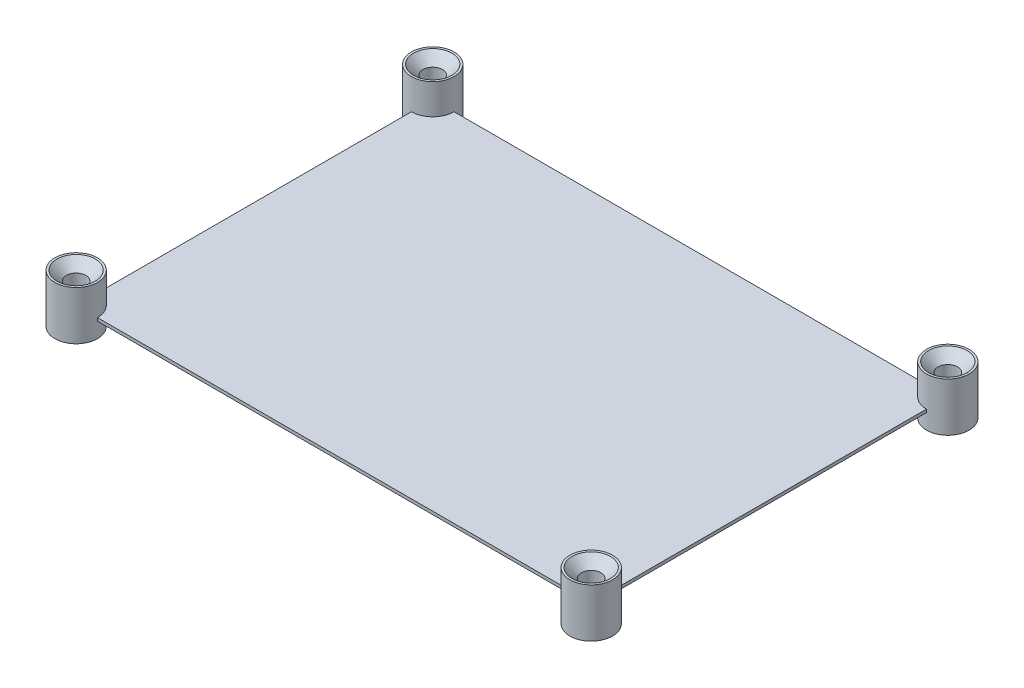
SolidWorks part; units mm, degrees
ref_plane "Front Plane" through (0, 0, 0) normal (0, 0, 1) x (1, 0, 0)
ref_plane "Top Plane" through (0, 0, 0) normal (0, 1, 0) x (1, 0, 0)
ref_plane "Right Plane" through (0, 0, 0) normal (1, 0, 0) x (0, 0, -1)
sketch "Sketch2" plane through (0, 0, 0) normal (0, 1, 0) x (1, 0, 0)
  line L1 (0, 0) -> (-84.5, 0)
  line L2 (0, 0) -> (0, -58.5)
  line L3 (0, -58.5) -> (-84.5, -58.5)
  line L4 (-84.5, 0) -> (-84.5, -58.5)
extrude "Boss-Extrude1" add sketch "Sketch2" along normal blind 0.5
sketch "Sketch3" plane through (0, 0.5, 0) normal (0, 1, 0) x (1, 0, 0)
  circle A0 centre (-84.5, 0) radius 3.5
  circle A1 centre (-84.5, 0) radius 3.5
sketch "Sketch5" plane through (0, 0.5, 0) normal (0, 1, 0) x (1, 0, 0)
  line L0 (-84.5, 0) -> (-84.5, -58.5) construction
  circle A0 centre (-84.5, -58.5) radius 3.5
  circle A1 centre (-84.5, -58.5) radius 3.5
sketch "Sketch6" plane through (0, 0.5, 0) normal (0, 1, 0) x (1, 0, 0)
  circle A0 centre (0, -58.5) radius 3.5
  circle A1 centre (0, -58.5) radius 3.5
sketch "Sketch7" plane through (0, 0.5, 0) normal (0, 1, 0) x (1, 0, 0)
  circle A0 centre (0, 0) radius 3.5
  circle A1 centre (0, 0) radius 3.5
extrude "Boss-Extrude2" add sketch "Sketch3" along normal blind 5 and the other way blind 3 contours A0
extrude "Boss-Extrude3" add sketch "Sketch5" along normal blind 5 and the other way blind 3 contours A0
extrude "Boss-Extrude4" add sketch "Sketch6" along normal blind 5 and the other way blind 3 contours A0
extrude "Boss-Extrude5" add sketch "Sketch7" along normal blind 5 and the other way blind 3 contours A0
hole_wizard "CSK for M3 Flat Head Machine Screw1" positions "Sketch9" profile "Sketch10" countersink size "M3" standard "ANSI Metric"
sketch "Sketch9" plane through (0, 5.5, 0) normal (0, 1, 0) x (1, 0, 0)
  point P0 (-84.5, 0)
sketch "Sketch10" plane through (-84.5, 5.5, 0) normal (1, 0, 0) x (0, 0, 1)
  line L0 (0, 0) -> (0, 14)
  line L1 (0, 14) -> (1.6, 13.0386)
  line L2 (1.6, 13.0386) -> (1.6, 1.55)
  line L3 (1.6, 1.55) -> (3.15, 0)
  line L5 (3.15, 0) -> (0, 0)
  line L6 (-1.6, 1.55) -> (-3.15, 0) construction
  line L10 (0, 14) -> (-1.6, 13.0386) construction
  line L11 (0, -6.35) -> (0, 107.95) construction
  dimension "Hole Dia." = 3.2
  dimension "Hole Depth" = 14
  dimension "Near C'Sink Dia." = 6.3
  dimension "Near C'Sink Angle" = 90
  dimension "Drill Angle" = 118
hole_wizard "CSK for M3 Flat Head Machine Screw2" positions "Sketch11" profile "Sketch12" countersink size "M3" standard "ANSI Metric"
sketch "Sketch11" plane through (0, 5.5, 0) normal (0, 1, 0) x (1, 0, 0)
  point P0 (-84.5, -58.5)
sketch "Sketch12" plane through (-84.5, 5.5, 58.5) normal (1, 0, 0) x (0, 0, 1)
  line L0 (0, 0) -> (0, 14)
  line L1 (0, 14) -> (1.6, 13.0386)
  line L2 (1.6, 13.0386) -> (1.6, 1.55)
  line L3 (1.6, 1.55) -> (3.15, 0)
  line L5 (3.15, 0) -> (0, 0)
  line L6 (-1.6, 1.55) -> (-3.15, 0) construction
  line L10 (0, 14) -> (-1.6, 13.0386) construction
  line L11 (0, -6.35) -> (0, 107.95) construction
  dimension "Hole Dia." = 3.2
  dimension "Hole Depth" = 14
  dimension "Near C'Sink Dia." = 6.3
  dimension "Near C'Sink Angle" = 90
  dimension "Drill Angle" = 118
hole_wizard "CSK for M3 Flat Head Machine Screw3" positions "Sketch15" profile "Sketch16" countersink size "M3" standard "ANSI Metric"
sketch "Sketch15" plane through (0, 5.5, 0) normal (0, 1, 0) x (1, 0, 0)
  point P0 (0, 0)
sketch "Sketch16" plane through (0, 5.5, 0) normal (1, 0, 0) x (0, 0, 1)
  line L0 (0, 0) -> (0, 14)
  line L1 (0, 14) -> (1.6, 13.0386)
  line L2 (1.6, 13.0386) -> (1.6, 1.55)
  line L3 (1.6, 1.55) -> (3.15, 0)
  line L5 (3.15, 0) -> (0, 0)
  line L6 (-1.6, 1.55) -> (-3.15, 0) construction
  line L10 (0, 14) -> (-1.6, 13.0386) construction
  line L11 (0, -6.35) -> (0, 107.95) construction
  dimension "Hole Dia." = 3.2
  dimension "Hole Depth" = 14
  dimension "Near C'Sink Dia." = 6.3
  dimension "Near C'Sink Angle" = 90
  dimension "Drill Angle" = 118
hole_wizard "CSK for M3 Flat Head Machine Screw4" positions "Sketch17" profile "Sketch18" countersink size "M3" standard "ANSI Metric"
sketch "Sketch17" plane through (0, 5.5, 0) normal (0, 1, 0) x (1, 0, 0)
  point P0 (0, -58.5)
sketch "Sketch18" plane through (0, 5.5, 58.5) normal (1, 0, 0) x (0, 0, 1)
  line L0 (0, 0) -> (0, 14)
  line L1 (0, 14) -> (1.6, 13.0386)
  line L2 (1.6, 13.0386) -> (1.6, 1.55)
  line L3 (1.6, 1.55) -> (3.15, 0)
  line L5 (3.15, 0) -> (0, 0)
  line L6 (-1.6, 1.55) -> (-3.15, 0) construction
  line L10 (0, 14) -> (-1.6, 13.0386) construction
  line L11 (0, -6.35) -> (0, 107.95) construction
  dimension "Hole Dia." = 3.2
  dimension "Hole Depth" = 14
  dimension "Near C'Sink Dia." = 6.3
  dimension "Near C'Sink Angle" = 90
  dimension "Drill Angle" = 118
